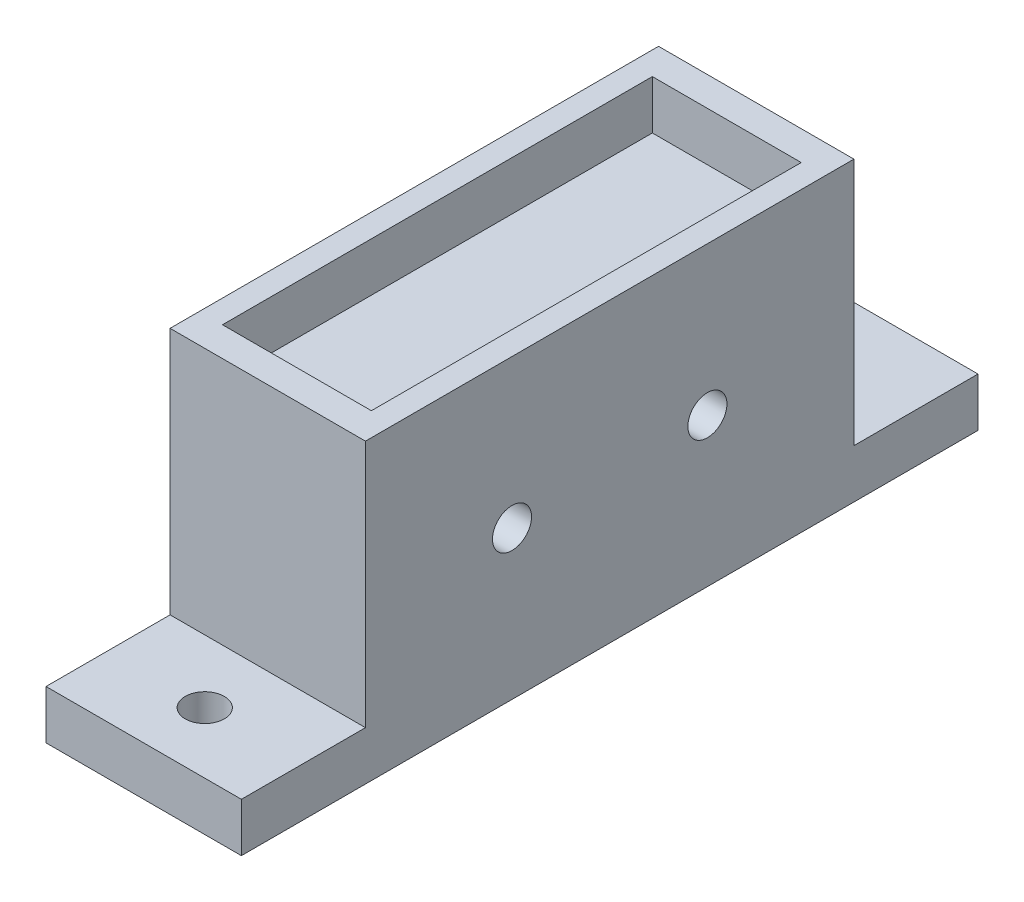
SolidWorks part; units mm, degrees
ref_plane "Front Plane" through (0, 0, 0) normal (0, 0, 1) x (1, 0, 0)
ref_plane "Top Plane" through (0, 0, 0) normal (0, 1, 0) x (1, 0, 0)
ref_plane "Right Plane" through (0, 0, 0) normal (1, 0, 0) x (0, 0, -1)
sketch "Sketch1" plane through (0, 0, 0) normal (1, 0, 0) x (0, 0, -1)
  line L0 (0, 0) -> (0, 5)
  line L1 (0, 5) -> (12.7, 5)
  line L2 (12.7, 5) -> (12.7, 30.4)
  line L3 (12.7, 30.4) -> (62.7, 30.4)
  line L4 (62.7, 30.4) -> (62.7, 5)
  line L5 (62.7, 5) -> (75.4, 5)
  line L6 (75.4, 5) -> (75.4, 0)
  line L7 (75.4, 0) -> (0, 0)
  dimension "D1" = 12.7
  dimension "D2" = 12.7
  dimension "D3" = 25.4
  dimension "D4" = 5
  dimension "D5" = 50
extrude "Boss-Extrude1" add sketch "Sketch1" along normal blind 20
sketch "Sketch2" plane through (0, 0, 0) normal (0, 1, 0) x (1, 0, 0)
  line L0 (-40.8574, 37.7) -> (56.8373, 37.7) construction
  line L5 (20, 62.7) -> (0, 62.7) construction
  line L6 (20, 12.7) -> (0, 12.7) construction
  line L7 (10, 91.4048) -> (10, -8.5958) construction
  line L8 (0, 62.7) -> (0, 12.7) construction
  line L9 (20, 62.7) -> (20, 12.7) construction
sketch "Sketch4" plane through (0, 30.4, 0) normal (0, 1, 0) x (1, 0, 0)
  line L0 (-40.8574, 37.7) -> (56.8373, 37.7) construction
  line L1 (2.3664, 59.7) -> (17.6064, 59.7)
  line L2 (2.3664, 59.7) -> (2.3664, 15.7)
  line L3 (2.3664, 15.7) -> (17.6064, 15.7)
  line L4 (17.6064, 59.7) -> (17.6064, 15.7)
  line L5 (2.3664, 59.7) -> (17.6064, 15.7) construction
  line L6 (2.3664, 15.7) -> (17.6064, 59.7) construction
  point P0 (9.9864, 37.7)
  dimension "D1" = 15.24
  dimension "D2" = 44
extrude "Cut-Extrude1" cut sketch "Sketch4" against normal blind 5
sketch "Sketch5" plane through (0, 5, 0) normal (0, 1, 0) x (1, 0, 0)
  line L0 (10, 91.4048) -> (10, -8.5958) construction
  line L1 (20, 75.4) -> (0, 75.4) construction
  line L2 (20, 0) -> (0, 0) construction
  circle A0 centre (10, 69.15) radius 2
  circle A1 centre (10, 6.25) radius 2
  dimension "D1" = 6.25
  dimension "D2" = 6.25
  dimension "D3" = 4
  dimension "D4" = 4
extrude "Cut-Extrude2" cut sketch "Sketch5" against normal blind 5
sketch "Sketch6" plane through (0, 0, 0) normal (1, 0, 0) x (0, 0, -1)
  line L0 (27.7, 38.9062) -> (27.7, -14.8826) construction
  line L1 (47.7, 38.9062) -> (47.7, -14.8826) construction
  line L2 (12.7, 30.4) -> (12.7, 5) construction
  line L4 (62.7, 5) -> (62.7, 30.4) construction
  line L5 (0, 15.2) -> (74.9325, 15.2) construction
  line L6 (62.7, 30.4) -> (12.7, 30.4) construction
  line L7 (91.4048, 0) -> (-8.5958, 0) construction
  circle A0 centre (27.7, 15.2) radius 2
  circle A1 centre (47.7, 15.2) radius 2
  dimension "D3" = 4
  dimension "D4" = 4
  dimension "D1" = 15
  dimension "D2" = 15
extrude "Cut-Extrude3" cut sketch "Sketch6" against normal blind 5 and the other way through all
